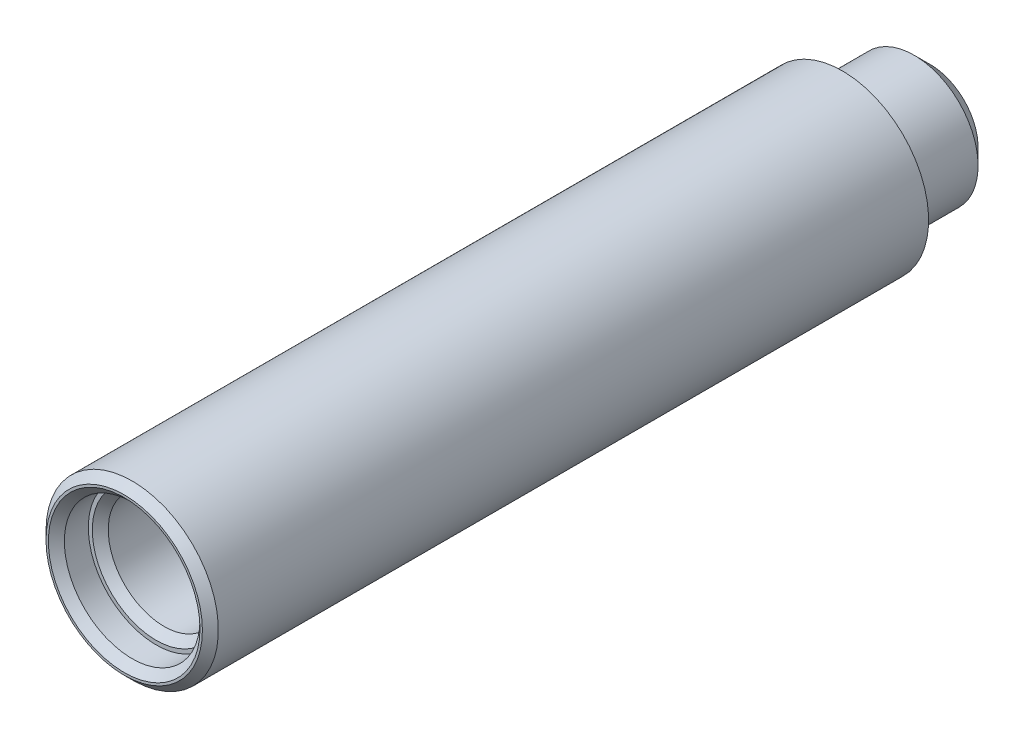
SolidWorks part; units mm, degrees
material "2A12"
ref_plane "前视基准面" through (0, 0, 0) normal (0, 0, 1) x (1, 0, 0)
ref_plane "上视基准面" through (0, 0, 0) normal (0, 1, 0) x (1, 0, 0)
ref_plane "右视基准面" through (0, 0, 0) normal (1, 0, 0) x (0, 0, -1)
sketch "草图1" plane through (0, 0, 0) normal (0, 0, 1) x (1, 0, 0)
  circle A0 centre (0, 0) radius 5.4
  dimension "D1" = 10.8
extrude "拉伸1" add sketch "草图1" along normal blind 45
sketch "草图2" plane through (0, 0, 45) normal (0, 0, 1) x (1, 0, 0)
  line L0 (0, 0) -> (0, -3.6) construction
  line L1 (-5, -3.6) -> (5, -3.6)
  line L2 (-5, -3.6) -> (-5, -5.6)
  line L3 (-5, -5.6) -> (5, -5.6)
  line L4 (5, -3.6) -> (5, -5.6)
  dimension "D1" = 3.6
  dimension "D2" = 10
  dimension "D3" = 2
extrude "拉伸2" [suppressed] cut sketch "草图2" against normal up to surface (40 mm away)
sketch "草图4" plane through (0, 0, 0) normal (0, -1, 0) x (1, 0, 0)
  line L0 (-22, 0) -> (22, 0)
  line L1 (-22, 0) -> (-28, -15.0512)
  line L4 (28, -15.0512) -> (22, 0)
  line L5 (0, 0) -> (0, -12) construction
  arc A0 (-28, -15.0512) -> (28, -15.0512) centre (0, -142) cw
  dimension "D3" = 130
  dimension "D1" = 44
  dimension "D2" = 12
  dimension "D4" = 56
extrude "拉伸3" add sketch "草图4" against normal mid plane 10.8
hole_wizard "M8x1.0 Tapped Hole1" positions "3D草图1" profile "草图5" tap size "M8x1.0" standard "GB"
sketch3d "3D草图1"
  line L0 (0, 0, 45) -> (0, 0, 0) construction
  point P0 (0, 0, 45)
sketch "草图5" plane through (0, 0, 45) normal (1, 0, 0) x (0, -1, 0)
  line L0 (0, 0) -> (0, 15.103)
  line L1 (0, 15.103) -> (3.5, 13)
  line L2 (3.5, 13) -> (3.5, 0)
  line L5 (3.5, 0) -> (0, 0)
  line L10 (0, 15.103) -> (-3.5, 13) construction
  line L11 (0, -6.35) -> (0, 107.95) construction
  dimension "螺纹孔钻头直径" = 7
  dimension "螺纹孔钻头深度" = 13
  dimension "导头角度" = 118
cosmetic thread "孔螺蚊线1" parameters "D1"=8, "D2"=8
sketch "草图6" plane through (0, 0, 0) normal (0, 0, 1) x (1, 0, 0)
  line L0 (-19.5, -1.4) -> (19.5, -1.4)
  line L1 (0, 0) -> (0, -1.4)
  line L3 (22, -5.4) -> (0, -5.4) construction
  dimension "D1" = 4
  dimension "D2" = 39
hole_wizard "M3 Tapped Hole1" positions "3D草图2" profile "草图7" tap size "M3" standard "GB"
sketch3d "3D草图2"
  point P0 (-19.5, -1.4, 0)
  point P3 (19.5, -1.4, 0)
sketch "草图7" plane through (-19.5, -1.4, 0) normal (1, 0, 0) x (0, -1, 0)
  line L0 (0, 0) -> (0, 8.2511)
  line L1 (0, 8.2511) -> (1.25, 7.5)
  line L2 (1.25, 7.5) -> (1.25, 0)
  line L5 (1.25, 0) -> (0, 0)
  line L10 (0, 8.2511) -> (-1.25, 7.5) construction
  line L11 (0, -6.35) -> (0, 107.95) construction
  dimension "螺纹孔钻头直径" = 2.5
  dimension "螺纹孔钻头深度" = 7.5
  dimension "导头角度" = 118
cosmetic thread "孔螺蚊线2" parameters "D1"=6, "D2"=3
cosmetic thread "孔螺蚊线3" parameters "D1"=6, "D2"=3
chamfer "倒角1" distance 0.5 angle 45 2 edges at (20.75, -1.4, 0) (-18.25, -1.4, 0)
chamfer "倒角2" distance 0.5 angle 45 1 edges at (5.4, 0, 45)
sketch "草图9" plane through (0, 0, 45) normal (0, 0, 1) x (1, 0, 0)
  circle A0 centre (0, 0) radius 4.25
  dimension "D1" = 8.5
extrude "拉伸5" cut sketch "草图9" against normal blind 2
chamfer "倒角3" distance 0.5 angle 45 2 edges at (4.25, 0, 45) (3.5, 0, 43)
sketch "草图10" plane through (0, 0, 0) normal (0, 0, 1) x (1, 0, 0)
  line L1 (45.4151, -17.2801) -> (-45.4151, -17.2801)
  line L2 (45.4151, -17.2801) -> (45.4151, 17.2801)
  line L3 (45.4151, 17.2801) -> (-45.4151, 17.2801)
  line L4 (-45.4151, -17.2801) -> (-45.4151, 17.2801)
  line L5 (45.4151, -17.2801) -> (-45.4151, 17.2801) construction
  line L6 (45.4151, 17.2801) -> (-45.4151, -17.2801) construction
  point P0 (0, 0)
extrude "切除-拉伸1" cut sketch "草图10" against normal blind 85
sketch "草图11" plane through (0, 0, 0) normal (0, 0, -1) x (-1, 0, 0)
  circle A0 centre (0, 0) radius 3.5
  dimension "D1" = 7
extrude "凸台-拉伸1" add sketch "草图11" along normal blind 0.5
sketch "草图12" plane through (0, 0, -0.5) normal (0, 0, -1) x (-1, 0, 0)
  circle A0 centre (0, 0) radius 4
  dimension "D1" = 8
extrude "凸台-拉伸2" add sketch "草图12" along normal blind 5
chamfer "倒角4" distance 1 angle 45 1 edges at (-4, 0, -5.5)
